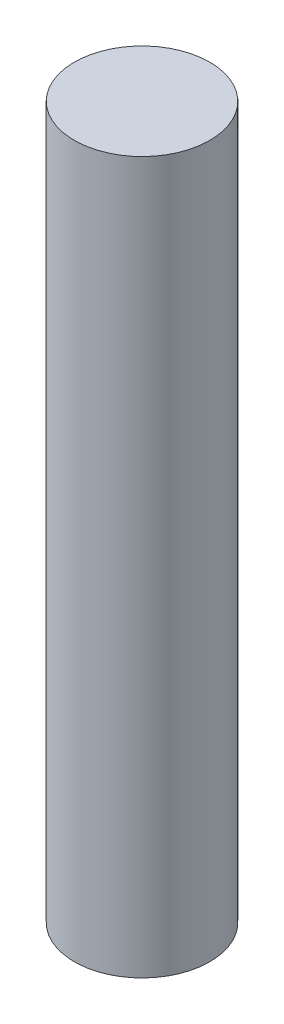
SolidWorks part; units mm, degrees
ref_plane "Front Plane" through (0, 0, 0) normal (0, 0, 1) x (1, 0, 0)
ref_plane "Top Plane" through (0, 0, 0) normal (0, 1, 0) x (1, 0, 0)
ref_plane "Right Plane" through (0, 0, 0) normal (1, 0, 0) x (0, 0, -1)
sketch "Sketch1" plane through (0, 0, 0) normal (0, 1, 0) x (1, 0, 0)
  circle A0 centre (0, 0) radius 1
  dimension "D1" = 2
extrude "Boss-Extrude1" add sketch "Sketch1" along normal blind 10.5
sketch "Sketch2" plane through (0, 10.5, 0) normal (0, 1, 0) x (1, 0, 0)
  circle A0 centre (0, 0) radius 1 construction
  point P0 (-0.2812, 0.9596)
